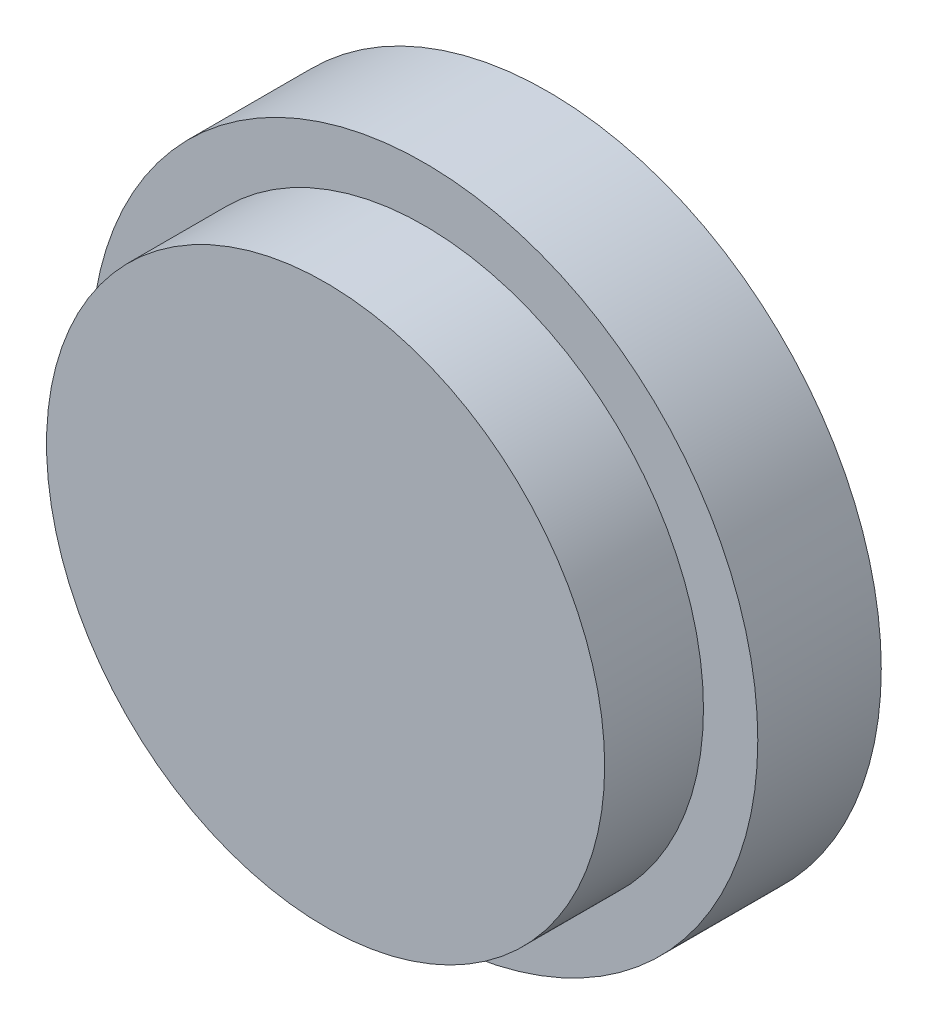
SolidWorks part; units mm, degrees
ref_plane "前视基准面" through (0, 0, 0) normal (0, 0, 1) x (1, 0, 0)
ref_plane "上视基准面" through (0, 0, 0) normal (0, 1, 0) x (1, 0, 0)
ref_plane "右视基准面" through (0, 0, 0) normal (1, 0, 0) x (0, 0, -1)
other "Configuration Table"
sketch "AICAD_SKETCH_F001" plane through (0, 0, 0) normal (0, 0, 1) x (1, 0, 0)
  circle A0 centre (0, 0) radius 13.5
  point P0 (0, 0)
  dimension "D1" = 13.5
extrude "AICAD_F001_BASE_EXTRUDE" add sketch "AICAD_SKETCH_F001" along normal blind 5
sketch "AICAD_SKETCH_F002" plane through (0, 0, 5) normal (0, 0, 1) x (1, 0, 0)
  circle A0 centre (0, 0) radius 11.3
  point P0 (0, 0)
  dimension "D1" = 11.3
extrude "AICAD_F002_BOSS_EXTRUDE" add sketch "AICAD_SKETCH_F002" along normal blind 4
